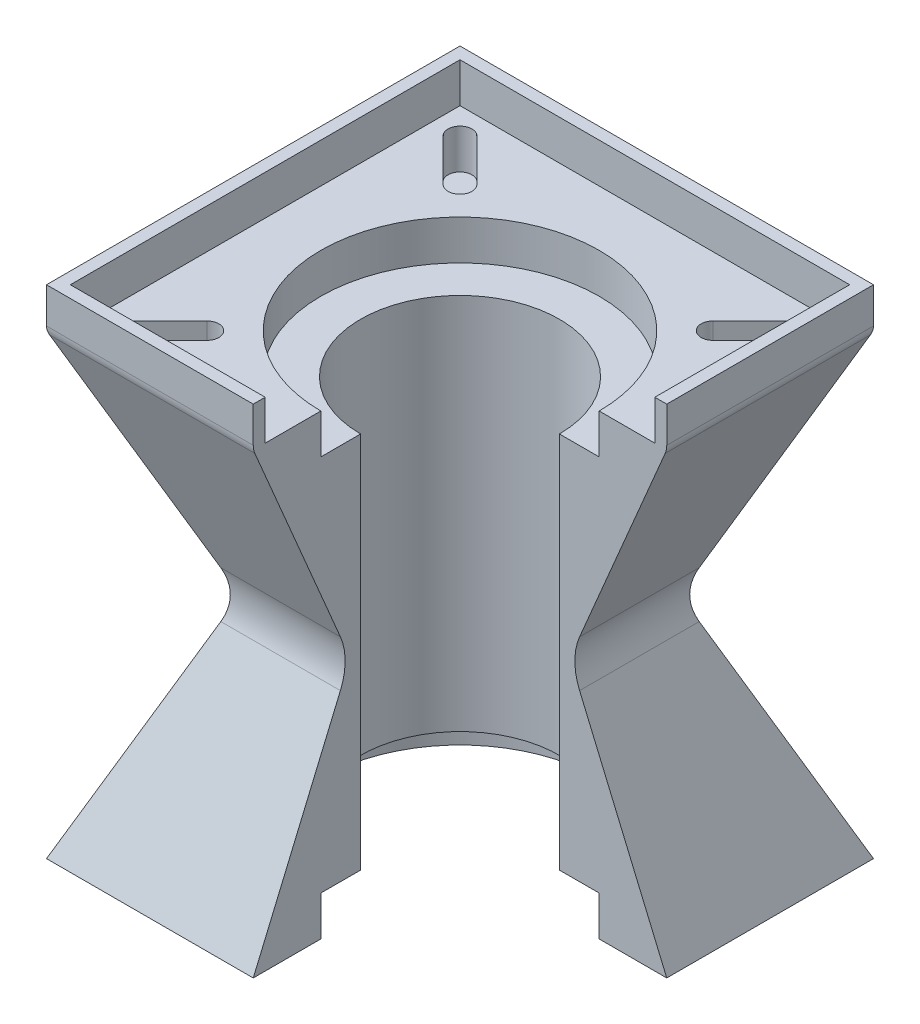
SolidWorks part; units mm, degrees
material "Cast Stainless Steel"
ref_plane "Front Plane" through (0, 0, 0) normal (0, 0, 1) x (1, 0, 0)
ref_plane "Top Plane" through (0, 0, 0) normal (0, 1, 0) x (1, 0, 0)
ref_plane "Right Plane" through (0, 0, 0) normal (1, 0, 0) x (0, 0, -1)
sketch "Sketch2" plane through (0, 0, 0) normal (0, 0, 1) x (1, 0, 0)
  line L0 (-55.1854, 0) -> (-79.5927, 57.5)
  line L1 (-79.5927, 57.5) -> (24.4073, 57.5)
  line L2 (24.4073, 57.5) -> (0, 0)
  line L6 (-55.1854, 0) -> (0, 0)
  line L7 (24.4073, -57.5) -> (0, 0)
  line L8 (-79.5927, -57.5) -> (24.4073, -57.5)
  line L9 (-55.1854, 0) -> (-79.5927, -57.5)
  dimension "D1" = 104
  dimension "D4" = 57.5
  dimension "D5" = 57.5
extrude "Boss-Extrude1" add sketch "Sketch2" along normal blind 104 contours L6 L9 L8 L7 | L0 L6 L2 L1
sketch "Sketch4" plane through (0, 0, 0) normal (1, 0, 0) x (0, 0, -1)
  line L0 (-104, 57.5) -> (-79.5927, 0)
  line L1 (-104, 0) -> (0, 0) construction
  line L2 (-79.5927, 0) -> (-104, -57.5)
  line L3 (-104, -57.5) -> (-104, 0) construction
  line L4 (-104, 57.5) -> (-104, 0) construction
  line L5 (-104, 57.5) -> (-104, -57.5)
  line L8 (-24.4073, 0) -> (0, -57.5)
  line L9 (0, 57.5) -> (-24.4073, 0)
  line L10 (0, 57.5) -> (0, -57.5)
  dimension "D1" = 23
  dimension "D2" = 23
extrude "Cut-Extrude1" cut sketch "Sketch4" along normal through all both and the other way through all
sketch "Sketch5" plane through (0, 57.5, 0) normal (0, 1, 0) x (1, 0, 0)
  circle A0 centre (-27.5927, -52) radius 25
  dimension "D1" = 50
extrude "Cut-Extrude2" cut sketch "Sketch5" against normal through all both
fillet "Fillet1" radius 15 4 edges at (-27.5927, 0, 79.5927) (-55.1854, 0, 52) (-27.5927, 0, 24.4073) (0, 0, 52)
sketch "Sketch6" plane through (0, 57.5, 0) normal (0, 1, 0) x (1, 0, 0)
  circle A0 centre (-27.5927, -52) radius 35
  dimension "D1" = 70
extrude "Cut-Extrude3" cut sketch "Sketch6" against normal blind 10
sketch "Sketch7" plane through (0, -57.5, 0) normal (0, -1, 0) x (1, 0, 0)
  circle A0 centre (-27.5927, 52) radius 35
  dimension "D1" = 70
extrude "Cut-Extrude4" cut sketch "Sketch7" against normal blind 10
sketch "Sketch8" plane through (0, 47.5, 0) normal (0, 1, 0) x (1, 0, 0)
  line L0 (-27.5927, -52) -> (24.4073, -52)
  line L1 (24.4073, -104) -> (24.4073, 0) construction
  line L2 (-27.5927, -52) -> (-27.5927, -104)
  line L3 (-79.5927, -104) -> (24.4073, -104) construction
  line L4 (-27.5927, -104) -> (24.4073, -104)
  line L5 (24.4073, -104) -> (24.4073, -52)
extrude "Cut-Extrude6" cut sketch "Sketch8" against normal through all both and the other way through all
sketch "Sketch9" plane through (0, 57.5, 0) normal (0, 1, 0) x (1, 0, 0)
  line L0 (24.4073, 0) -> (-79.5927, 0)
  line L1 (-79.5927, 0) -> (-79.5927, -104)
  line L2 (-79.5927, -104) -> (-27.5927, -104)
  line L3 (-27.5927, -104) -> (-27.5927, -101)
  line L4 (-27.5927, -87) -> (-27.5927, -104) construction
  line L5 (-27.5927, -101) -> (-76.5927, -101)
  line L6 (-76.5927, -101) -> (-76.5927, -3)
  line L7 (-76.5927, -3) -> (21.4073, -3)
  line L8 (21.4073, -3) -> (21.4073, -52)
  line L9 (24.4073, -52) -> (7.4073, -52) construction
  line L10 (21.4073, -52) -> (24.4073, -52)
  line L11 (24.4073, -52) -> (24.4073, 0)
  dimension "D1" = 3
  dimension "D2" = 3
  dimension "D3" = 3
  dimension "D4" = 3
extrude "Boss-Extrude2" add sketch "Sketch9" along normal blind 10
fillet "Fillet2" radius 5 4 edges at (24.4073, 57.5, 26) (-27.5927, 57.5, 0) (-79.5927, 57.5, 52) (-53.5927, 57.5, 104)
sketch "Sketch10" plane through (0, 57.5, 0) normal (0, 1, 0) x (1, 0, 0)
  line L0 (-27.5927, -77) -> (-27.5927, -52)
  line L1 (-72.1514, -11.684) -> (-61.5448, -22.2906)
  line L2 (-67.9087, -7.4413) -> (-57.3021, -18.0479)
  line L3 (12.7233, -7.4413) -> (2.1167, -18.0479)
  line L4 (-66.8481, -16.9873) -> (-64.7268, -14.8659)
  line L5 (16.966, -11.684) -> (6.3594, -22.2906)
  line L8 (-67.9087, -96.5587) -> (-57.3021, -85.9521)
  line L9 (-72.1514, -92.316) -> (-61.5448, -81.7094)
  arc A0 (-67.9087, -7.4413) -> (-72.1514, -11.684) centre (-70.0301, -9.5626) ccw
  arc A1 (-61.5448, -22.2906) -> (-57.3021, -18.0479) centre (-59.4235, -20.1692) ccw
  arc A2 (16.966, -11.684) -> (12.7233, -7.4413) centre (14.8447, -9.5626) ccw
  arc A3 (2.1167, -18.0479) -> (6.3594, -22.2906) centre (4.2381, -20.1692) ccw
  arc A6 (-72.1514, -92.316) -> (-67.9087, -96.5587) centre (-70.0301, -94.4374) ccw
  arc A7 (-57.3021, -85.9521) -> (-61.5448, -81.7094) centre (-59.4235, -83.8308) ccw
  point P33 (-27.5927, -52)
  dimension "D1" = 6
  dimension "D2" = 6
  dimension "D3" = 15
extrude "Cut-Extrude7" cut sketch "Sketch10" against normal blind 10
